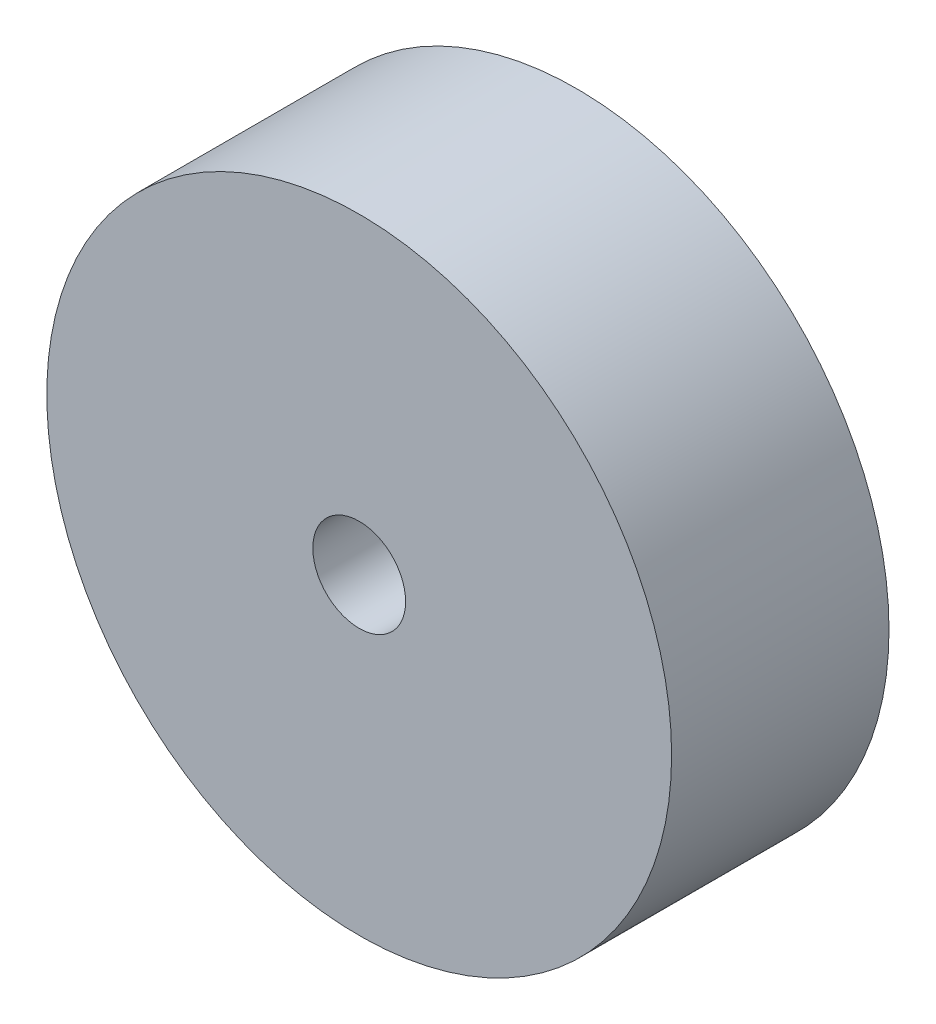
SolidWorks part; units mm, degrees
ref_plane "Alzado" through (0, 0, 0) normal (0, 0, 1) x (1, 0, 0)
ref_plane "Planta" through (0, 0, 0) normal (0, 1, 0) x (1, 0, 0)
ref_plane "Vista lateral" through (0, 0, 0) normal (1, 0, 0) x (0, 0, -1)
sketch "Croquis1" plane through (0, 0, 0) normal (0, 0, 1) x (1, 0, 0)
  circle A0 centre (0, 0) radius 27.275
  dimension "D1" = 54.55
extrude "Saliente-Extruir1" add sketch "Croquis1" along normal mid plane 18.98
sketch "Croquis2" plane through (0, 0, -9.49) normal (0, 0, -1) x (-1, 0, 0)
  circle A0 centre (0, 0) radius 4.05
  dimension "D1" = 8.1
extrude "Cortar-Extruir3" cut sketch "Croquis2" against normal blind 66 contours A0
